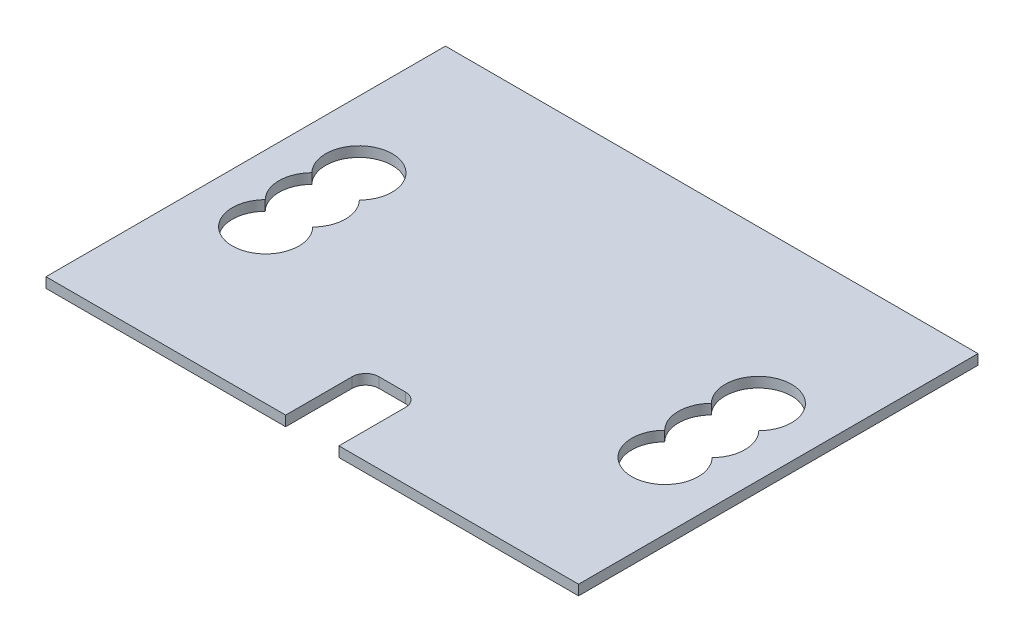
SolidWorks part; units mm, degrees
ref_plane "Front Plane" through (0, 0, 0) normal (0, 0, 1) x (1, 0, 0)
ref_plane "Top Plane" through (0, 0, 0) normal (0, 1, 0) x (1, 0, 0)
ref_plane "Right Plane" through (0, 0, 0) normal (1, 0, 0) x (0, 0, -1)
sketch "Sketch1" plane through (0, 0, 0) normal (0, 1, 0) x (1, 0, 0)
  line L1 (0, 0) -> (400, 0)
  line L2 (0, 0) -> (0, 300)
  line L3 (0, 300) -> (400, 300)
  line L4 (400, 0) -> (400, 300)
  dimension "D1" = 400
  dimension "D2" = 300
extrude "Boss-Extrude1" add sketch "Sketch1" along normal blind 7.62
sketch "Sketch2" plane through (0, 7.62, 0) normal (0, 1, 0) x (1, 0, 0)
  line L0 (400, 300) -> (0, 300) construction
  line L1 (0, 300) -> (0, 0) construction
  line L2 (0, 0) -> (400, 0) construction
  line L3 (200, 300) -> (200, 0) construction
  arc A0 (32.172, 167.526) -> (32.172, 132.474) centre (50, 150) ccw
  arc A2 (67.828, 167.526) -> (32.172, 167.526) centre (50, 185.052) ccw
  arc A3 (32.172, 132.474) -> (67.828, 132.474) centre (50, 114.948) ccw
  arc A4 (67.828, 132.474) -> (67.828, 167.526) centre (50, 150) ccw
  arc A5 (367.828, 167.526) -> (367.828, 132.474) centre (350, 150) cw
  arc A6 (332.172, 167.526) -> (367.828, 167.526) centre (350, 185.052) cw
  arc A7 (332.172, 132.474) -> (332.172, 167.526) centre (350, 150) cw
  arc A8 (367.828, 132.474) -> (332.172, 132.474) centre (350, 114.948) cw
  dimension "D2" = 50
  dimension "D1" = 150
  dimension "D3" = 50
  dimension "D4" = 2
  dimension "D5" = 2
extrude "Cut-Extrude1" cut sketch "Sketch2" against normal blind 7.62
sketch "Sketch3" plane through (0, 7.62, 0) normal (0, 1, 0) x (1, 0, 0)
  line L0 (200, 300) -> (200, 0) construction
  line L1 (400, 300) -> (0, 300) construction
  line L2 (0, 0) -> (400, 0) construction
  line L4 (180, 0) -> (220, 0)
  line L5 (180, 0) -> (180, 50)
  line L6 (190, 60) -> (210, 60)
  line L7 (220, 0) -> (220, 50)
  line L8 (180, 0) -> (220, 60) construction
  line L9 (180, 60) -> (220, 0) construction
  arc A0 (180, 50) -> (190, 60) centre (190, 50) cw
  arc A1 (210, 60) -> (220, 50) centre (210, 50) cw
  point P6 (200, 30)
  dimension "D2" = 10
  dimension "D1" = 40
extrude "Cut-Extrude2" cut sketch "Sketch3" against normal blind 7.62
